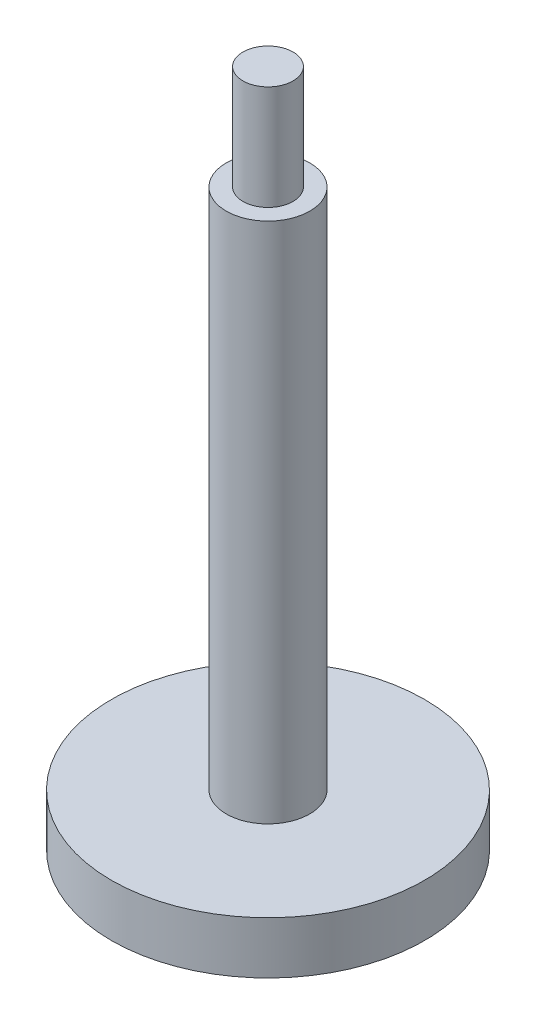
SolidWorks part; units mm, degrees
ref_plane "Alzado" through (0, 0, 0) normal (0, 0, 1) x (1, 0, 0)
ref_plane "Planta" through (0, 0, 0) normal (0, 1, 0) x (1, 0, 0)
ref_plane "Vista lateral" through (0, 0, 0) normal (1, 0, 0) x (0, 0, -1)
sketch "Croquis1" plane through (0, 0, 0) normal (1, 0, 0) x (0, 0, -1)
  line L0 (0, 0) -> (-2.4, 0)
  line L1 (-2.4, 0) -> (-2.4, -10)
  line L2 (-2.4, -10) -> (-4, -10)
  line L3 (-4, -10) -> (-4, -60)
  line L4 (-4, -60) -> (-15, -60)
  line L5 (-15, -60) -> (-15, -65)
  line L6 (-15, -65) -> (0, -65)
  line L7 (0, -65) -> (0, 0) construction
  line L8 (0, 0) -> (0, -65)
  point P4 (0, 0)
  point P11 (0.922, 0)
  dimension "D1" = 10
  dimension "D2" = 2.4
  dimension "D3" = 50
  dimension "D4" = 4
  dimension "D5" = 15
  dimension "D6" = 5
revolve "Revolución1" add sketch "Croquis1" angle 360 about L7
sketch "Croquis2" plane through (0, -65, 0) normal (0, -1, 0) x (1, 0, 0)
  circle A0 centre (0, 0) radius 1.35
  dimension "D1" = 2.7
extrude "Cortar-Extruir1" cut sketch "Croquis2" against normal blind 20
